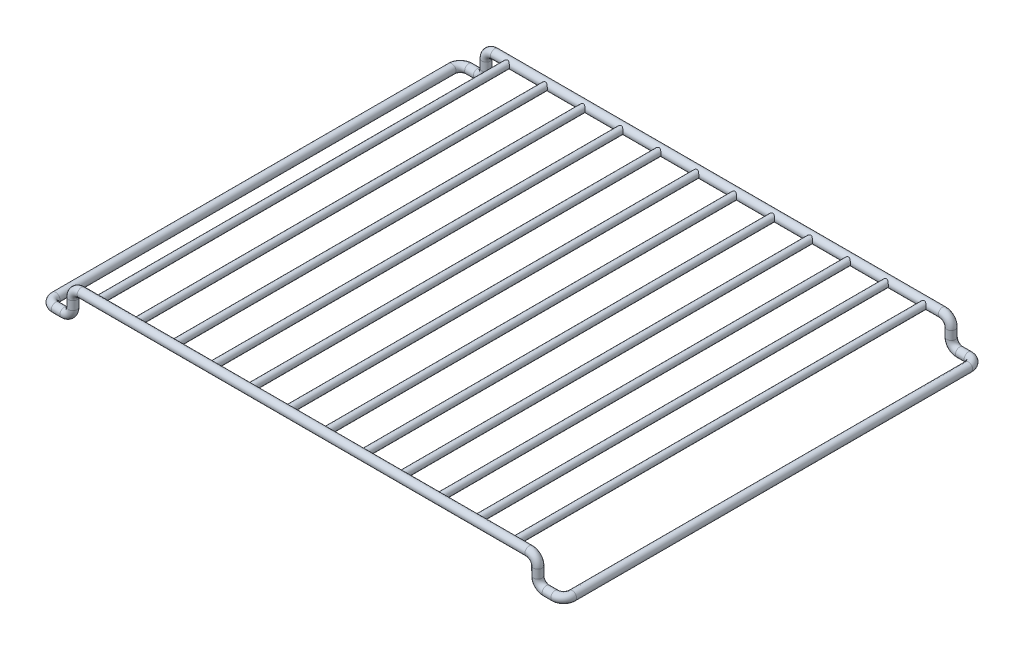
SolidWorks part; units mm, degrees
ref_plane "Front" through (0, 0, 0) normal (0, 0, 1) x (1, 0, 0)
ref_plane "Top" through (0, 0, 0) normal (0, 1, 0) x (1, 0, 0)
ref_plane "Right" through (0, 0, 0) normal (1, 0, 0) x (0, 0, -1)
sketch3d "Трехмерный эскиз2"
  line L0 (0, 0, 0) -> (130, 0, 0)
  line L1 (135, -5, 0) -> (135, -10, 0)
  line L2 (140, -15, 0) -> (145, -15, 0)
  line L3 (150, -15, -5) -> (150, -15, -235)
  line L4 (145, -15, -240) -> (140, -15, -240)
  line L5 (135, -10, -240) -> (135, -5, -240)
  line L6 (130, 0, -240) -> (0, 0, -240)
  arc A0 (135, -5, -240) -> (130, 0, -240) centre (130, -5, -240) ccw
  arc A1 (140, -15, -240) -> (135, -10, -240) centre (140, -10, -240) ccw
  arc A2 (150, -15, -235) -> (145, -15, -240) centre (145, -15, -235) ccw
  arc A3 (145, -15, 0) -> (150, -15, -5) centre (145, -15, -5) ccw
  arc A4 (135, -10, 0) -> (140, -15, 0) centre (140, -10, 0) ccw
  arc A5 (130, 0, 0) -> (135, -5, 0) centre (130, -5, 0) ccw
  point P11 (135, 0, -240)
  point P12 (130, -5, -235)
  point P15 (135, -15, -240)
  point P16 (140, -10, -245)
  point P19 (150, -15, -240)
  point P20 (145, -10, -235)
  point P23 (150, -15, 0)
  point P24 (145, -10, -5)
  point P27 (135, -15, 0)
  point P28 (140, -10, 5)
  point P31 (135, 0, 0)
  point P32 (130, -5, -5)
  dimension "D8" = 5
  dimension "D1" = 135
  dimension "D2" = 15
  dimension "D3" = 15
  dimension "D4" = 240
  dimension "D5" = 15
  dimension "D6" = 15
  dimension "D7" = 135
sketch "Эскиз1" plane through (0, 0, 0) normal (1, 0, 0) x (0, 0, -1)
  circle A0 centre (0, 0) radius 2.5
sweep "По траектории1" add profiles "Эскиз1" path "Трехмерный эскиз2"
sketch "Эскиз3" plane through (0, 0, 0) normal (0, 0, 1) x (1, 0, 0)
  circle A0 centre (11, 0) radius 2
  dimension "D1" = 11
  dimension "D2" = 4
extrude "Бобышка-Вытянуть1" add sketch "Эскиз3" against normal up to surface (237.5 mm away) up to face at (130, 0, -237.5)
pattern_linear "Линейный массив1" count 6 spacing 22 along (1, 0, 0) of "Бобышка-Вытянуть1"
mirror "Зеркальное отражение1" about plane through (0, 0, 0) normal (1, 0, 0) of bodies 103
